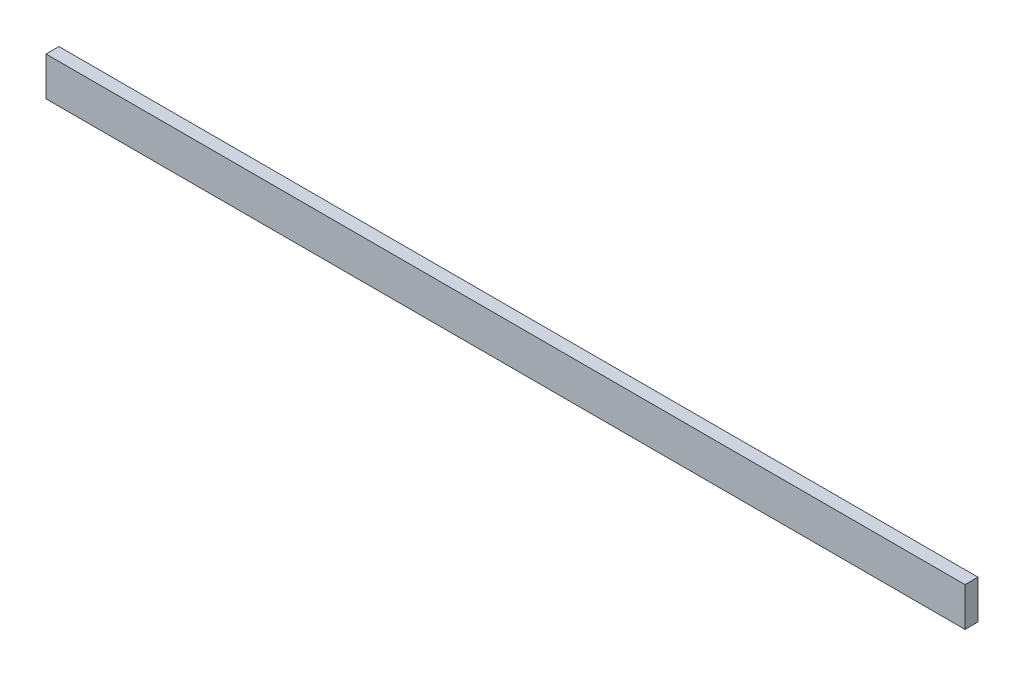
SolidWorks part; units mm, degrees
ref_plane "Front Plane" through (0, 0, 0) normal (0, 0, 1) x (1, 0, 0)
ref_plane "Top Plane" through (0, 0, 0) normal (0, 1, 0) x (1, 0, 0)
ref_plane "Right Plane" through (0, 0, 0) normal (1, 0, 0) x (0, 0, -1)
sketch "Sketch1" plane through (0, 0, 0) normal (0, 0, 1) x (1, 0, 0)
  line L1 (0, 0) -> (901.7, 0)
  line L2 (0, 0) -> (0, 38.1)
  line L3 (0, 38.1) -> (901.7, 38.1)
  line L4 (901.7, 0) -> (901.7, 38.1)
  dimension "D1" = 901.7
  dimension "D2" = 38.1
extrude "Boss-Extrude1" add sketch "Sketch1" along normal blind 12.7
